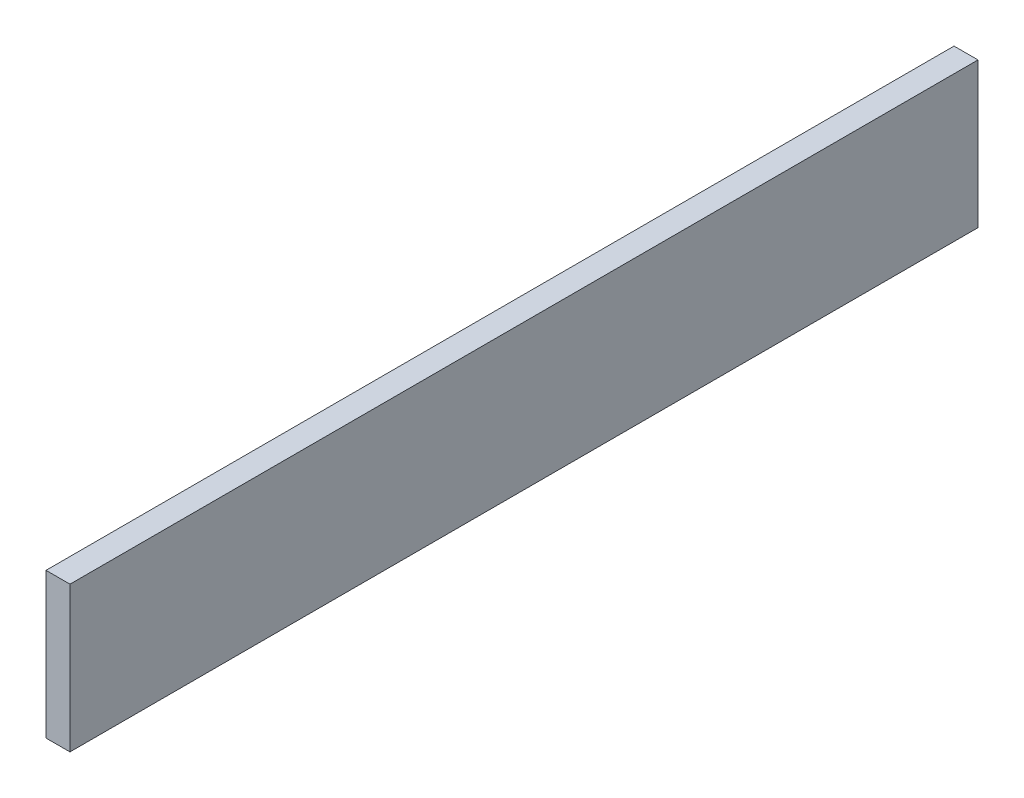
SolidWorks part; units mm, degrees
material "Pinho"
ref_plane "Plano frontal" through (0, 0, 0) normal (0, 0, 1) x (1, 0, 0)
ref_plane "Plano superior" through (0, 0, 0) normal (0, 1, 0) x (1, 0, 0)
ref_plane "Plano direito" through (0, 0, 0) normal (1, 0, 0) x (0, 0, -1)
sketch "Esboço1" plane through (0, 0, 0) normal (0, 0, 1) x (1, 0, 0)
  line L1 (-9.9, -60) -> (9.9, -60)
  line L2 (-9.9, -60) -> (-9.9, 60)
  line L3 (-9.9, 60) -> (9.9, 60)
  line L4 (9.9, -60) -> (9.9, 60)
  line L5 (-9.9, -60) -> (9.9, 60) construction
  line L6 (-9.9, 60) -> (9.9, -60) construction
  point P0 (0, 0)
  dimension "D1" = 120
  dimension "D2" = 19.8
extrude "Ressalto-extrusão1" add sketch "Esboço1" against normal blind 750
